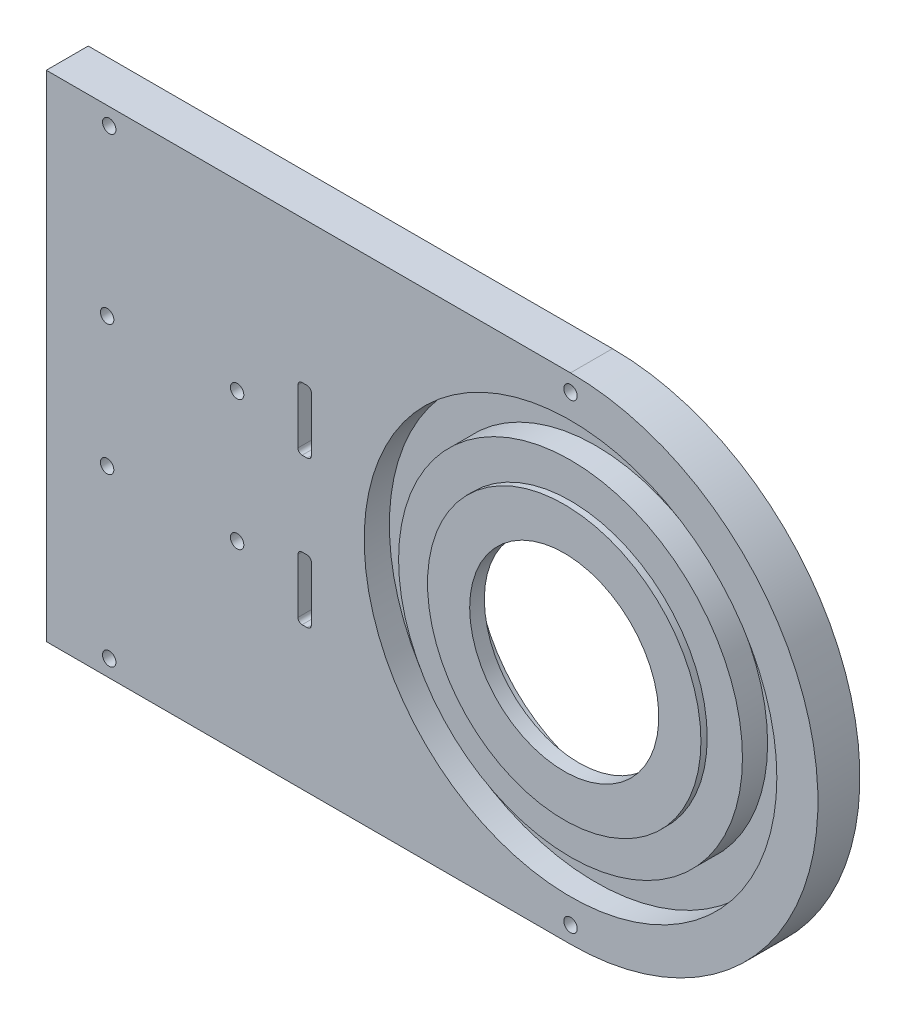
SolidWorks part; units mm, degrees
material "Custom Plastic"
ref_plane "Front Plane" through (0, 0, 0) normal (0, 0, 1) x (1, 0, 0)
ref_plane "Top Plane" through (0, 0, 0) normal (0, 1, 0) x (1, 0, 0)
ref_plane "Right Plane" through (0, 0, 0) normal (1, 0, 0) x (0, 0, -1)
sketch "Sketch1" plane through (0, 0, 0) normal (0, 0, 1) x (1, 0, 0)
  line L0 (-125, 59) -> (0, 59)
  line L1 (-125, -59) -> (-125, 59)
  line L2 (0, -59) -> (-125, -59)
  arc A0 (0, -59) -> (0, 59) centre (0, 0) ccw
  dimension "D1" = 59
  dimension "D2" = 125
  dimension "D3" = 118
extrude "Boss-Extrude1" add sketch "Sketch1" along normal blind 10
sketch "Sketch2" plane through (0, 0, 10) normal (0, 0, 1) x (1, 0, 0)
  circle A0 centre (0, 0) radius 32.6
  arc A3 (0, -59) -> (0, 59) centre (0, 0) ccw construction
  arc A4 (0, -59) -> (0, 59) centre (0, 0) ccw construction
  dimension "D1" = 65.2
extrude "Boss-Extrude2" add sketch "Sketch2" along normal blind 1.5
sketch "Sketch3" plane through (0, 0, 10) normal (0, 0, 1) x (1, 0, 0)
  circle A0 centre (0, 0) radius 22.5
  circle A1 centre (0, 0) radius 32.6 construction
  circle A2 centre (0, 0) radius 32.6
  dimension "D1" = 45
extrude "Cut-Extrude1" cut sketch "Sketch3" along normal blind 8 from surface at -10 contours A0 | A2 starting at face at (-47.75, 0, 0)
sketch "Sketch4" plane through (0, 0, 10) normal (0, 0, 1) x (1, 0, 0)
  line L3 (-125, 59) -> (-125, -59)
  line L7 (-125, 59) -> (-125, -59)
  line L10 (-125, -59) -> (0, -59)
  line L12 (-125, -59) -> (0, -59)
  line L13 (0, 59) -> (-125, 59)
  line L14 (0, 59) -> (-125, 59)
  arc A1 (0, -59) -> (0, 59) centre (0, 0) ccw
  arc A10 (0, -59) -> (0, 59) centre (0, 0) ccw
  dimension "D1" = 0
sketch "Sketch5" plane through (0, 0, 10) normal (0, 0, 1) x (1, 0, 0)
  arc A0 (0, -59) -> (0, 59) centre (0, 0) ccw construction
  circle A1 centre (0, 0) radius 45 construction
  circle A3 centre (0, 0) radius 49.2
  circle A4 centre (0, 0) radius 41
  point P29 (0, 0)
  dimension "D1" = 90
  dimension "D2" = 4.2
  dimension "D3" = 4
sketch "Sketch6" plane through (0, 0, 10) normal (0, 0, 1) x (1, 0, 0)
  line L2 (-125, -59) -> (-125, 59) construction
  line L3 (-125, 59) -> (0, 59) construction
  line L5 (0, -59) -> (-125, -59) construction
  circle A0 centre (0, -55) radius 1.6
  circle A1 centre (-110, -55) radius 1.6
  circle A2 centre (-110, 55) radius 1.6
  circle A3 centre (0, 55) radius 1.6
  dimension "D1" = 3.2
  dimension "D2" = 3.2
  dimension "D3" = 3.2
  dimension "D4" = 3.2
  dimension "D5" = 15
  dimension "D6" = 4
  dimension "D7" = 4
extrude "Cut-Extrude4" cut sketch "Sketch6" against normal up to surface (10 mm away) up to face at (32.6, 0, 0)
sketch "Sketch7" plane through (0, 0, 0) normal (0, 0, -1) x (-1, 0, 0)
  line L0 (125, -59) -> (125, 59) construction
  line L2 (0, 0) -> (95, 0) construction
  circle A0 centre (95, 0) radius 8.55
  dimension "D1" = 17.1
  dimension "D2" = 30
extrude "Cut-Extrude5" cut sketch "Sketch7" against normal blind 7.5
extrude "Cut-Extrude7" cut sketch "Sketch5" against normal blind 6
sketch "Sketch9" plane through (0, 0, 0) normal (0, 0, -1) x (-1, 0, 0)
  line L0 (95, 0) -> (95, 59) construction
  line L1 (125, 59) -> (0, 59) construction
  line L2 (95, 0) -> (0, 0) construction
  line L3 (79.5, 0) -> (110.5, 0) construction
  line L4 (79.5, -15.5) -> (110.5, -15.5) construction
  line L5 (79.5, -15.5) -> (79.5, 15.5) construction
  line L6 (79.5, 15.5) -> (110.5, 15.5) construction
  line L7 (110.5, -15.5) -> (110.5, 15.5) construction
  circle A1 centre (79.5, -15.5) radius 1.6
  circle A2 centre (79.5, 15.5) radius 1.6
  circle A3 centre (110.5, 15.5) radius 1.6
  circle A4 centre (110.5, -15.5) radius 1.6
  point P13 (95, 0)
  dimension "D1" = 31
  dimension "D3" = 3.2
  dimension "D4" = 4
  dimension "D2" = 31
extrude "Cut-Extrude8" cut sketch "Sketch9" against normal through all
sketch "Sketch10" plane through (0, 0, 0) normal (0, 0, -1) x (-1, 0, 0)
  circle A0 centre (0, 0) radius 22.55
  dimension "D1" = 45.1
extrude "Cut-Extrude9" cut sketch "Sketch10" against normal through all
sketch "Sketch11" plane through (0, 0, 0) normal (0, 0, -1) x (-1, 0, 0)
  line L0 (8.2529, 31.5381) -> (97.1645, 8.2715) construction
  line L1 (97.1645, -8.2715) -> (8.2529, -31.5381) construction
  line L2 (0, 0) -> (95, 0) construction
  line L3 (65, -24) -> (65, -11)
  line L4 (62.8, 25) -> (64, 25)
  line L5 (61.8, 24) -> (61.8, 11)
  line L6 (62.8, 10) -> (64, 10)
  line L7 (65, 24) -> (65, 11)
  line L8 (62.8, -10) -> (64, -10)
  line L9 (61.8, -24) -> (61.8, -11)
  line L10 (62.8, -25) -> (64, -25)
  circle A0 centre (0, 0) radius 32.6 construction
  circle A1 centre (0, 0) radius 32.6 construction
  circle A2 centre (95, 0) radius 8.55 construction
  circle A3 centre (95, 0) radius 8.55 construction
  circle A4 centre (95, 0) radius 8.55 construction
  arc A5 (64, 25) -> (65, 24) centre (64, 24) cw
  arc A6 (62.8, 10) -> (61.8, 11) centre (62.8, 11) cw
  arc A7 (64, 10) -> (65, 11) centre (64, 11) ccw
  arc A8 (62.8, 25) -> (61.8, 24) centre (62.8, 24) ccw
  arc A9 (62.8, -25) -> (61.8, -24) centre (62.8, -24) cw
  arc A10 (64, -10) -> (65, -11) centre (64, -11) cw
  arc A11 (62.8, -10) -> (61.8, -11) centre (62.8, -11) ccw
  arc A12 (64, -25) -> (65, -24) centre (64, -24) ccw
  point P16 (63.4, 10)
  point P19 (65, 25)
  point P22 (61.8, 10)
  point P25 (65, 10)
  point P40 (65, -10)
  point P41 (61.8, -10)
  point P42 (65, -25)
  dimension "D5" = 1
  dimension "D1" = 3.2
  dimension "D2" = 15
  dimension "D3" = 30
  dimension "D4" = 10
extrude "Cut-Extrude10" cut sketch "Sketch11" against normal through all
